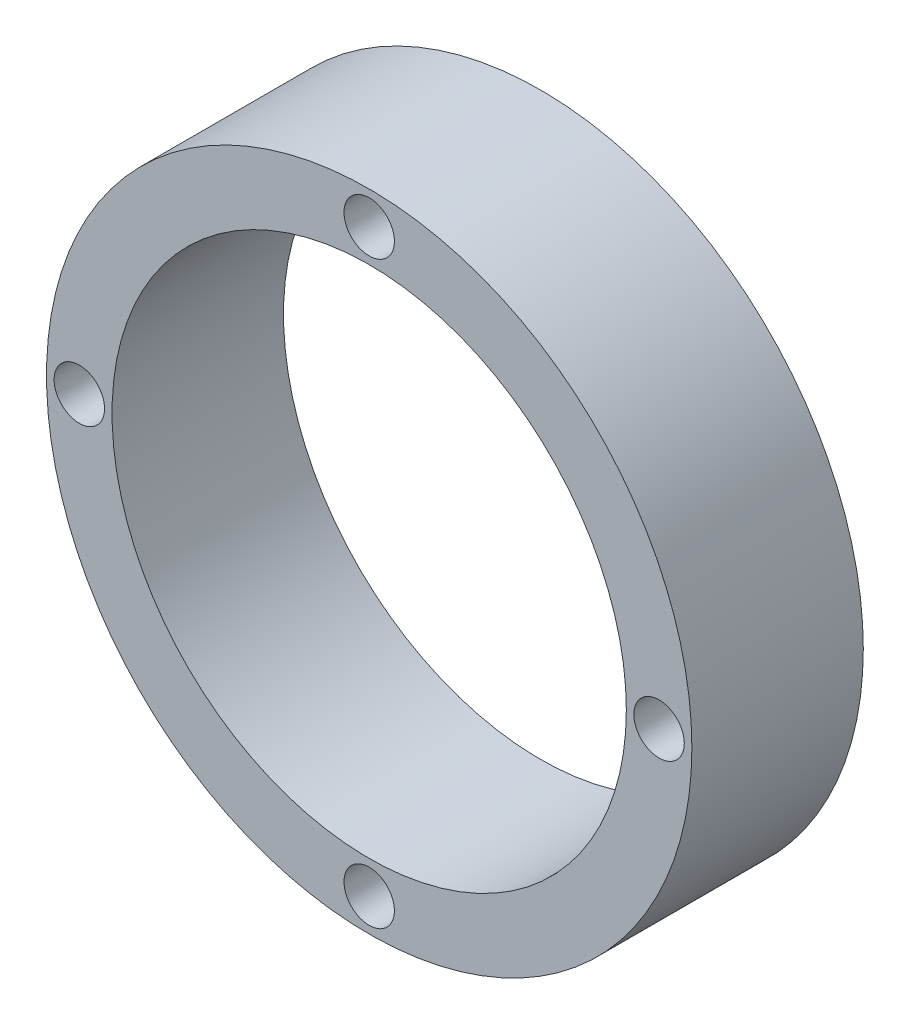
SolidWorks part; units mm, degrees
ref_plane "Front Plane" through (0, 0, 0) normal (0, 0, 1) x (1, 0, 0)
ref_plane "Top Plane" through (0, 0, 0) normal (0, 1, 0) x (1, 0, 0)
ref_plane "Right Plane" through (0, 0, 0) normal (1, 0, 0) x (0, 0, -1)
sketch "Sketch1" plane through (0, 0, 0) normal (0, 0, 1) x (1, 0, 0)
  circle A0 centre (0, 0) radius 32
  circle A1 centre (0, 0) radius 25.5
  circle A3 centre (0, 0) radius 28.7454 construction
  circle A4 centre (0, 28.7454) radius 2.5
  circle A5 centre (28.7454, 0) radius 2.5
  circle A6 centre (0, -28.7454) radius 2.5
  circle A7 centre (-28.7454, 0) radius 2.5
  dimension "D1" = 64
  dimension "D2" = 51
  dimension "D3" = 5
  dimension "D4" = 4
extrude "Boss-Extrude1" add sketch "Sketch1" along normal blind 17
